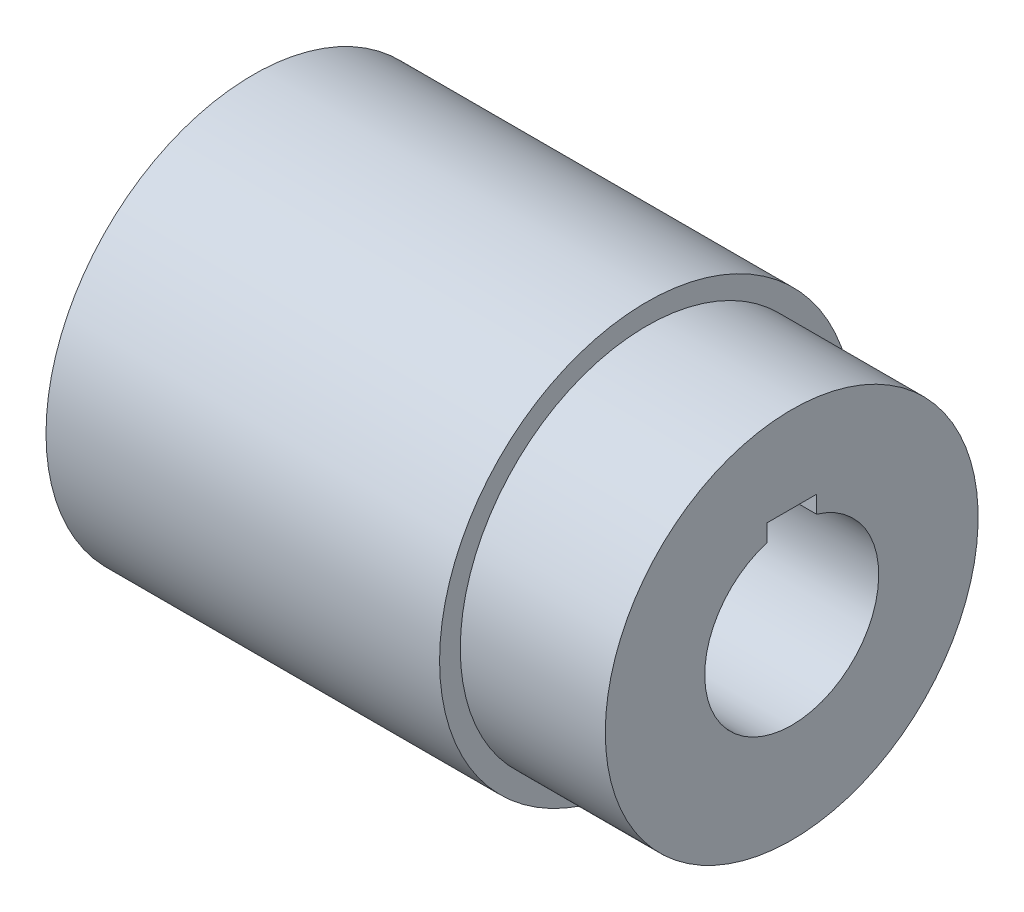
SolidWorks part; units mm, degrees
material "ASTM A36 Steel"
ref_plane "Front Plane" through (0, 0, 0) normal (0, 0, 1) x (1, 0, 0)
ref_plane "Top Plane" through (0, 0, 0) normal (0, 1, 0) x (1, 0, 0)
ref_plane "Right Plane" through (0, 0, 0) normal (1, 0, 0) x (0, 0, -1)
sketch "Sketch1" plane through (0, 0, 0) normal (1, 0, 0) x (0, 0, -1)
  circle A0 centre (0, 0) radius 50
  circle A1 centre (0, 0) radius 21
  dimension "D1" = 42
  dimension "D2" = 100
extrude "Boss-Extrude1" add sketch "Sketch1" along normal blind 130
sketch "Sketch2" plane through (0, 0, 0) normal (-1, 0, 0) x (0, 0, 1)
  line L1 (-6, 17.7) -> (6, 17.7)
  line L2 (-6, 17.7) -> (-6, 24.3)
  line L3 (-6, 24.3) -> (6, 24.3)
  line L4 (6, 17.7) -> (6, 24.3)
  line L5 (-6, 17.7) -> (6, 24.3) construction
  line L6 (-6, 24.3) -> (6, 17.7) construction
  circle A0 centre (0, 0) radius 21 construction
  point P0 (0, 21)
  dimension "D1" = 6.6
  dimension "D2" = 12
extrude "Cut-Extrude1" cut sketch "Sketch2" against normal through all both and the other way through all
sketch "Sketch3" plane through (0, 0, 0) normal (0, 1, 0) x (1, 0, 0)
  line L0 (0, 0) -> (144.6856, 0)
  line L1 (130, -50) -> (95, -50)
  line L2 (130, -50) -> (130, -45)
  line L3 (130, -45) -> (95, -45)
  line L4 (95, -50) -> (95, -45)
  dimension "D1" = 35
  dimension "D2" = 45
revolve "Cut-Revolve1" cut sketch "Sketch3" angle 360 about L0
sketch "Sketch4" plane through (0, 0, 0) normal (-1, 0, 0) x (0, 0, 1)
  circle A0 centre (0, 0) radius 32.5
  dimension "D1" = 65
extrude "Cut-Extrude2" cut sketch "Sketch4" against normal blind 20
sketch "Sketch5" plane through (0, 0, 0) normal (-1, 0, 0) x (0, 0, 1)
  line L0 (-42.5, 0) -> (-58.1503, 0)
  circle A0 centre (0, 0) radius 42.5
  dimension "D1" = 85
hole_wizard "M8x1.0 Tapped Hole1" positions "3DSketch1" profile "Sketch7" tap size "M8x1.0" standard "DIN"
sketch3d "3DSketch1"
  circle A0 centre (0, 0, 0) radius 42.5 construction
  point P0 (0, 0, -42.5)
  point P5 (0, 0, 42.5)
  point P8 (-42.5, 0, 0)
sketch "Sketch7" plane through (0, 0, -42.5) normal (0, 1, 0) x (0, 0, 1)
  line L0 (0, 0) -> (0, 42.103)
  line L1 (0, 42.103) -> (3.5, 40)
  line L2 (3.5, 40) -> (3.5, 0.525)
  line L3 (3.5, 0.525) -> (4.025, 0)
  line L5 (4.025, 0) -> (0, 0)
  line L6 (-3.5, 0.525) -> (-4.025, 0) construction
  line L10 (0, 42.103) -> (-3.5, 40) construction
  line L11 (0, -6.35) -> (0, 107.95) construction
  dimension "Tap Drill Dia." = 7
  dimension "Tap Drill Depth" = 40
  dimension "Near C'Sink Dia." = 8.05
  dimension "Near C'Sink Angle" = 90
  dimension "Drill Angle" = 118
cosmetic thread "Hole Thread1"
cosmetic thread "Hole Thread2"
sketch "Sketch8" plane through (0, 0, 0) normal (-1, 0, 0) x (0, 0, 1)
  circle A0 centre (0, 0) radius 42.5
